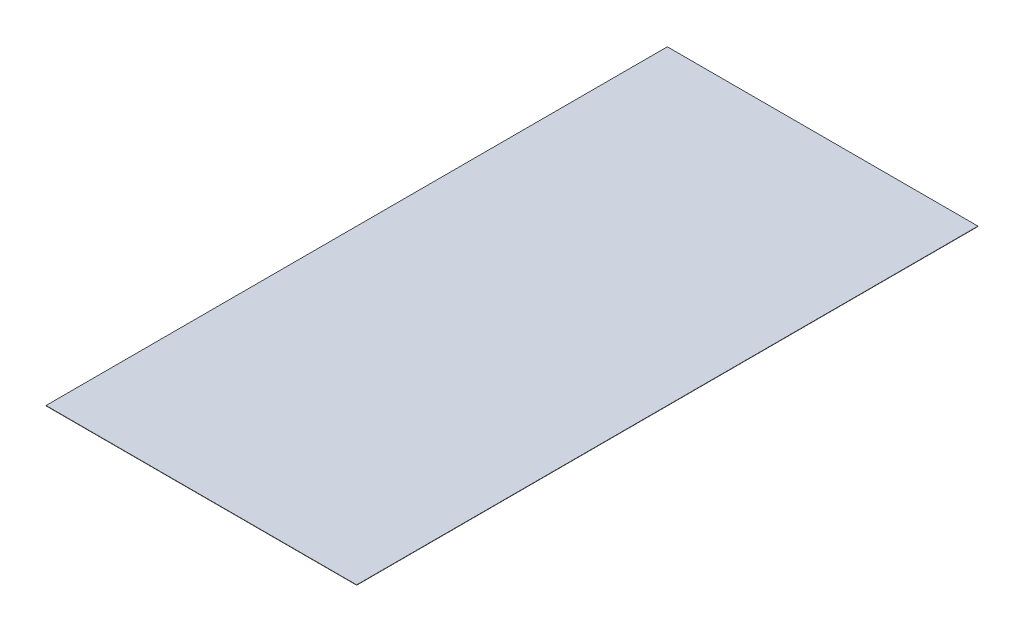
SolidWorks part; units mm, degrees
ref_plane "Front Plane" through (0, 0, 0) normal (0, 0, 1) x (1, 0, 0)
ref_plane "Top Plane" through (0, 0, 0) normal (0, 1, 0) x (1, 0, 0)
ref_plane "Right Plane" through (0, 0, 0) normal (1, 0, 0) x (0, 0, -1)
sketch "Sketch1" plane through (0, 0, 0) normal (0, 1, 0) x (1, 0, 0)
  line L1 (-609.6, 1219.2) -> (609.6, 1219.2)
  line L2 (-609.6, 1219.2) -> (-609.6, -1219.2)
  line L3 (-609.6, -1219.2) -> (609.6, -1219.2)
  line L4 (609.6, 1219.2) -> (609.6, -1219.2)
  line L5 (-609.6, 1219.2) -> (609.6, -1219.2) construction
  line L6 (-609.6, -1219.2) -> (609.6, 1219.2) construction
  point P0 (0, 0)
  dimension "D1" = 2438.4
  dimension "D2" = 1219.2
extrude "Boss-Extrude1" add sketch "Sketch1" along normal blind 1.24
